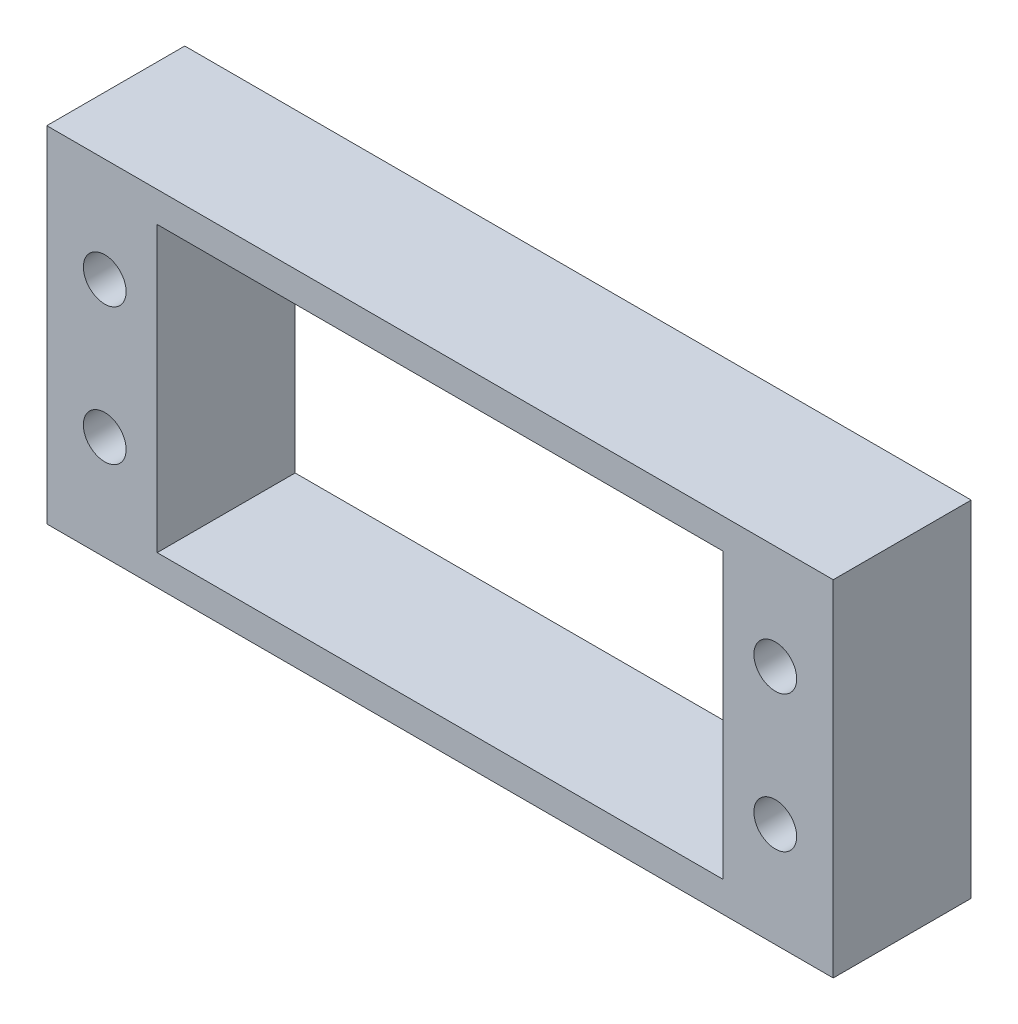
SolidWorks part; units mm, degrees
ref_plane "前视基准面" through (0, 0, 0) normal (0, 0, 1) x (1, 0, 0)
ref_plane "上视基准面" through (0, 0, 0) normal (0, 1, 0) x (1, 0, 0)
ref_plane "右视基准面" through (0, 0, 0) normal (1, 0, 0) x (0, 0, -1)
sketch "草图1" plane through (0, 0, 0) normal (0, 0, 1) x (1, 0, 0)
  line L0 (0, 0) -> (31.2771, 0) construction
  line L1 (0, 0) -> (0, 9.6949) construction
  line L3 (-20.5, -10.3) -> (20.5, -10.3)
  line L4 (-20.5, -10.3) -> (-20.5, 10.3)
  line L5 (-20.5, 10.3) -> (20.5, 10.3)
  line L6 (20.5, -10.3) -> (20.5, 10.3)
  line L7 (-20.5, -10.3) -> (20.5, 10.3) construction
  line L8 (-20.5, 10.3) -> (20.5, -10.3) construction
  line L9 (-28.5, -12.5) -> (28.5, -12.5)
  line L10 (-28.5, -12.5) -> (-28.5, 12.5)
  line L11 (-28.5, 12.5) -> (28.5, 12.5)
  line L12 (28.5, -12.5) -> (28.5, 12.5)
  line L13 (-28.5, -12.5) -> (28.5, 12.5) construction
  line L14 (-28.5, 12.5) -> (28.5, -12.5) construction
  circle A0 centre (24.3, 4.95) radius 1.55
  circle A1 centre (-24.3, 4.95) radius 1.55
  circle A2 centre (-24.3, -4.95) radius 1.55
  circle A3 centre (24.3, -4.95) radius 1.55
  dimension "D1" = 3.1
  dimension "D2" = 24.3
  dimension "D3" = 4.95
  dimension "D4" = 41
  dimension "D5" = 20.6
  dimension "D6" = 57
  dimension "D7" = 25
extrude "凸台-拉伸1" add sketch "草图1" along normal blind 10
